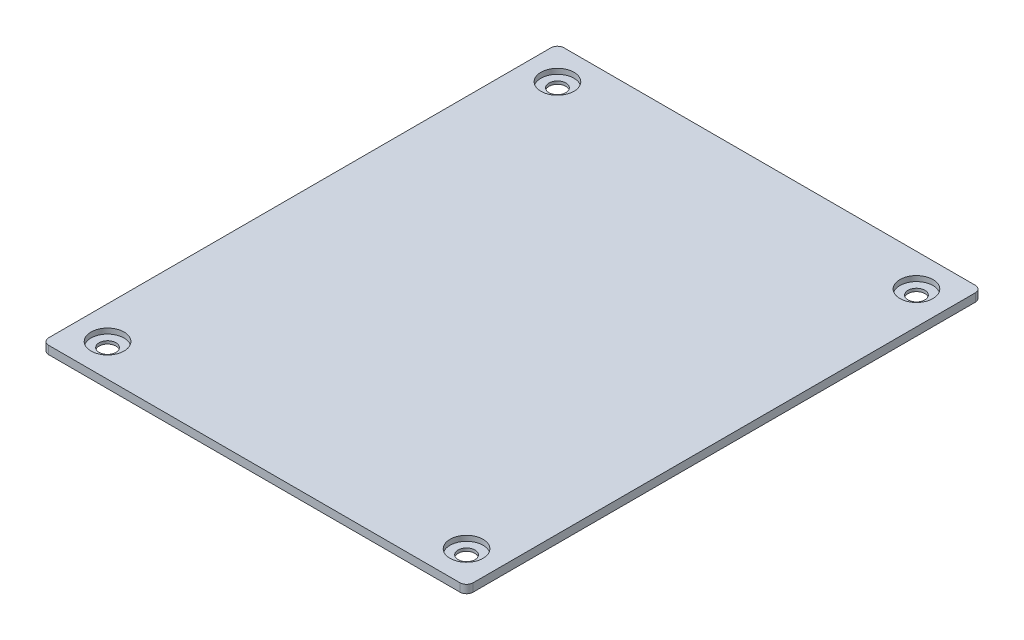
SolidWorks part; units mm, degrees
material "AISI 316 Stainless Steel Sheet (SS)"
ref_plane "Front Plane" through (0, 0, 0) normal (0, 0, 1) x (1, 0, 0)
ref_plane "Top Plane" through (0, 0, 0) normal (0, 1, 0) x (1, 0, 0)
ref_plane "Right Plane" through (0, 0, 0) normal (1, 0, 0) x (0, 0, -1)
sketch "Sketch1" plane through (0, 0, 0) normal (0, 1, 0) x (1, 0, 0)
  line L1 (-82.423, -100.076) -> (82.423, -100.076)
  line L2 (-82.423, -100.076) -> (-82.423, 100.076)
  line L3 (-82.423, 100.076) -> (82.423, 100.076)
  line L4 (82.423, -100.076) -> (82.423, 100.076)
  line L5 (-82.423, -100.076) -> (82.423, 100.076) construction
  line L6 (-82.423, 100.076) -> (82.423, -100.076) construction
  point P0 (0, 0)
  dimension "D1" = 164.846
  dimension "D2" = 200.152
extrude "Boss-Extrude1" add sketch "Sketch1" along normal blind 3.175
hole_wizard "CBORE for 1/4 Socket Head Cap Screw1" positions "Sketch2" profile "Sketch3" counterbore size "1/4" standard "ANSI Inch" end condition through all
sketch "Sketch2" plane through (0, 3.175, 0) normal (0, 1, 0) x (-1, 0, 0)
  line L11 (82.423, 100.076) -> (-82.423, -100.076) construction
  line L14 (-69.723, 87.376) -> (69.723, 87.376) construction
  line L15 (-69.723, 87.376) -> (-69.723, -87.376) construction
  line L16 (-69.723, -87.376) -> (69.723, -87.376) construction
  line L17 (69.723, 87.376) -> (69.723, -87.376) construction
  line L18 (-69.723, 87.376) -> (69.723, -87.376) construction
  line L19 (-69.723, -87.376) -> (69.723, 87.376) construction
  line L20 (-82.423, 100.076) -> (-82.423, -100.076) construction
  line L21 (82.423, 100.076) -> (-82.423, 100.076) construction
  line L22 (-82.423, -100.076) -> (82.423, -100.076) construction
  line L23 (82.423, -100.076) -> (82.423, 100.076) construction
  point P282 (69.723, -87.376)
  point P319 (-69.723, 87.376)
  point P320 (-69.723, -87.376)
  point P321 (69.723, 87.376)
  dimension "D1" = 12.7
  dimension "D2" = 12.7
  dimension "D3" = 12.7
  dimension "D4" = 12.7
sketch "Sketch3" plane through (-69.723, 3.175, 87.376) normal (1, 0, 0) x (0, 0, 1)
  line L0 (0, 0) -> (0, 3.175)
  line L1 (0, 3.175) -> (3.2639, 3.175)
  line L3 (3.2639, 3.175) -> (3.2639, 2.032)
  line L4 (3.2639, 2.032) -> (6.4135, 2.032)
  line L5 (6.4135, 2.032) -> (6.4135, 0)
  line L7 (6.4135, 0) -> (0, 0)
  line L11 (0, -6.35) -> (0, 107.95) construction
  dimension "Thru Hole Dia." = 6.5278
  dimension "Thru Hole Depth" = 3.175
  dimension "C'Bore Dia." = 12.827
  dimension "C'Bore Depth" = 2.032
fillet "Fillet1" radius 2.54 4 edges at (-82.423, 1.5875, 100.076) (-82.423, 1.5875, -100.076) (82.423, 1.5875, -100.076) (82.423, 1.5875, 100.076)
equation "\"var01\"=0.5"
equation "\"D2@Sketch2\"=\"var01\""
equation "\"D1@Sketch2\"=\"var01\""
